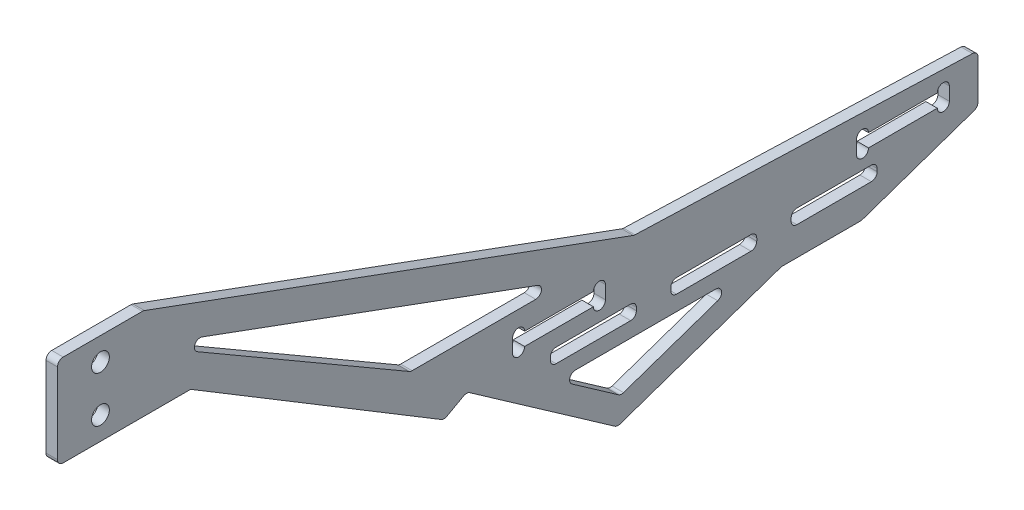
SolidWorks part; units mm, degrees
material "Thornel Mat VMA"
ref_plane "前视基准面" through (0, 0, 0) normal (0, 0, 1) x (1, 0, 0)
ref_plane "上视基准面" through (0, 0, 0) normal (0, 1, 0) x (1, 0, 0)
ref_plane "右视基准面" through (0, 0, 0) normal (1, 0, 0) x (0, 0, -1)
sketch "草图1" plane through (0, 0, 0) normal (1, 0, 0) x (0, 0, -1)
  line L0 (-7.5, 12) -> (-7.5, -4)
  line L2 (60, -30) -> (153.1, -30) construction
  line L3 (153.1, -30) -> (153.1, -21.5)
  line L5 (75.2504, -25.5) -> (165.6103, -25.5) construction
  line L6 (-7.5, 12) -> (7.5, 12)
  line L7 (88.1, -26.65) -> (71.9, -26.65)
  line L8 (88.1, -26.65) -> (88.1, -24.35)
  line L9 (88.1, -24.35) -> (71.9, -24.35)
  line L10 (71.9, -26.65) -> (71.9, -24.35)
  line L11 (88.1, -26.65) -> (71.9, -24.35) construction
  line L12 (88.1, -24.35) -> (71.9, -26.65) construction
  line L13 (148.1, -26.65) -> (131.9, -26.65)
  line L14 (148.1, -26.65) -> (148.1, -24.35)
  line L15 (148.1, -24.35) -> (131.9, -24.35)
  line L16 (131.9, -26.65) -> (131.9, -24.35)
  line L17 (148.1, -26.65) -> (131.9, -24.35) construction
  line L18 (148.1, -24.35) -> (131.9, -26.65) construction
  line L20 (-7.5, -4) -> (7.5, -4)
  line L22 (7, 6.8576) -> (54.1052, -20.5)
  line L23 (54.1052, -20.5) -> (81.5686, -20.5)
  line L24 (81.5686, -20.5) -> (7, 6.8576)
  line L34 (7.5, 12) -> (153.1, -21.5) construction
  line L35 (7.5, 12) -> (93.1, -19.4048)
  line L36 (93.1, -19.4048) -> (153.1, -21.5)
  line L42 (153.1, -30) -> (90.1544, -46.8662) construction
  line L45 (90.1544, -46.8662) -> (63.9247, -28.5)
  line L46 (63.9247, -28.5) -> (59.9247, -30.7038)
  line L47 (7.5, -4) -> (15.7391, -4)
  line L48 (15.7391, -4) -> (59.9247, -30.7038)
  line L51 (79.6815, -34.65) -> (113.3467, -34.65)
  line L52 (113.3467, -34.65) -> (90.7791, -42.4206)
  line L53 (90.7791, -42.4206) -> (79.6815, -34.65)
  line L54 (118.808, -37) -> (132.7705, -37)
  line L55 (93.5, -32) -> (78.5, -32)
  line L56 (93.5, -32) -> (93.5, -29.5)
  line L57 (93.5, -29.5) -> (78.5, -29.5)
  line L58 (78.5, -32) -> (78.5, -29.5)
  line L59 (93.5, -32) -> (78.5, -29.5) construction
  line L60 (93.5, -29.5) -> (78.5, -32) construction
  line L61 (114.5, -32) -> (99.5, -32)
  line L62 (114.5, -32) -> (114.5, -29.5)
  line L63 (114.5, -29.5) -> (99.5, -29.5)
  line L64 (99.5, -32) -> (99.5, -29.5)
  line L65 (114.5, -32) -> (99.5, -29.5) construction
  line L66 (114.5, -29.5) -> (99.5, -32) construction
  line L67 (135.5, -32) -> (120.5, -32)
  line L68 (135.5, -32) -> (135.5, -29.5)
  line L69 (135.5, -29.5) -> (120.5, -29.5)
  line L70 (120.5, -32) -> (120.5, -29.5)
  line L71 (135.5, -32) -> (120.5, -29.5) construction
  line L72 (135.5, -29.5) -> (120.5, -32) construction
  line L73 (132.7705, -37) -> (153.1, -30)
  line L74 (118.808, -37) -> (90.1544, -46.8662)
  circle A0 centre (0, 0) radius 1.55
  circle A1 centre (0, 8) radius 1.55
  circle A2 centre (132.95, -24.35) radius 1.05
  circle A3 centre (147.05, -24.35) radius 1.05
  circle A4 centre (132.95, -26.65) radius 1.05
  circle A5 centre (147.05, -26.65) radius 1.05
  circle A6 centre (72.95, -24.35) radius 1.05
  circle A7 centre (87.05, -24.35) radius 1.05
  circle A8 centre (87.05, -26.65) radius 1.05
  circle A9 centre (72.95, -26.65) radius 1.05
  point P10 (140, -25.5)
  point P13 (80, -25.5)
  point P38 (107, -30.75)
  point P47 (86, -30.75)
  point P63 (128, -30.75)
  dimension "D2" = 3.1
  dimension "D8" = 2.1
  dimension "D1" = 8
  dimension "D3" = 7.5
  dimension "D4" = 60
  dimension "D5" = 80
  dimension "D6" = 2.3
  dimension "D7" = 16.2
  dimension "D9" = 25.5
  dimension "D10" = 4.5
  dimension "D11" = 20
  dimension "D12" = 5
  dimension "D13" = 4
  dimension "D14" = 4
  dimension "D15" = 15
  dimension "D16" = 4
  dimension "D17" = 7
  dimension "D18" = 2
  dimension "D19" = 60
  dimension "D20" = 5
  dimension "D21" = 5
  dimension "D22" = 5
  dimension "D23" = 10
  dimension "D24" = 1
  dimension "D25" = 120
  dimension "D26" = 35
  dimension "D27" = 4
  dimension "D28" = 5
  dimension "D29" = 15
  dimension "D30" = 8
  dimension "D31" = 4
  dimension "D32" = 3
  dimension "D33" = 2.5
  dimension "D34" = 15
  dimension "D35" = 4
  dimension "D36" = 6
  dimension "D37" = 6
  dimension "D38" = 6
  dimension "D39" = 4
  dimension "D40" = 4
  dimension "D41" = 176
extrude "凸台-拉伸1" add sketch "草图1" along normal blind 2
fillet "圆角1" radius 1 30 edges at (1, -20.5, -81.5686) (1, -20.5, -54.1052) (1, 6.8576, -7) (1, -19.4048, -93.1) (1, -28.5, -63.9247) (1, -4, -15.7391) (1, -42.4206, -90.7791) (1, -32, -93.5) (1, -29.5, -93.5) (1, -29.5, -78.5) (1, -32, -78.5) (1, -32, -114.5) (1, -29.5, -114.5) (1, -29.5, -99.5) (1, -32, -99.5) (1, -32, -135.5) (1, -29.5, -135.5) (1, -29.5, -120.5) (1, -32, -120.5) (1, -34.65, -113.3467) (1, -34.65, -79.6815) (1, -30.7038, -59.9247) (1, -4, 7.5) (1, 12, 7.5) (1, 12, -7.5) (1, -21.5, -153.1) (1, -30, -153.1) (1, -37, -132.7705) (1, -37, -118.808) (1, -46.8662, -90.1544)
